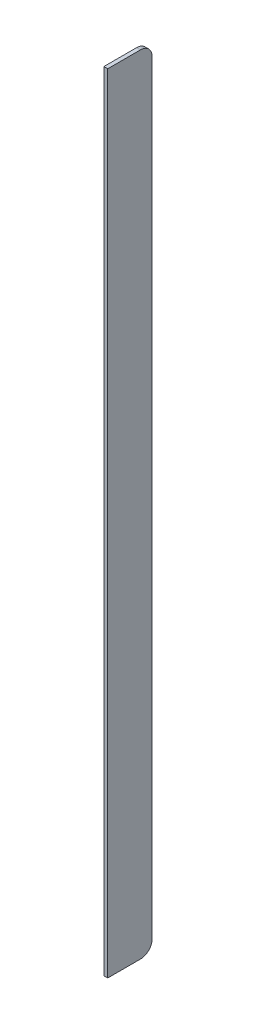
SolidWorks part; units mm, degrees
ref_plane "Front Plane" through (0, 0, 0) normal (0, 0, 1) x (1, 0, 0)
ref_plane "Top Plane" through (0, 0, 0) normal (0, 1, 0) x (1, 0, 0)
ref_plane "Right Plane" through (0, 0, 0) normal (1, 0, 0) x (0, 0, -1)
ref_plane "Plane4" through (-48, 0, 0) normal (-1, 0, 0) x (0, -1, 0)
sketch "Sketch1" plane through (-48, 0, 0) normal (-1, 0, 0) x (0, -1, 0)
  line L0 (-99, -47) -> (99, -47)
  line L1 (102, -44) -> (102, -35.5)
  line L2 (102, -35.5) -> (-102, -35.5)
  line L3 (-102, -35.5) -> (-102, -44)
  arc A0 (-102, -44) -> (-99, -47) centre (-99, -44) ccw
  arc A1 (99, -47) -> (102, -44) centre (99, -44) ccw
extrude "Boss-Extrude1" add sketch "Sketch1" against normal blind 1
